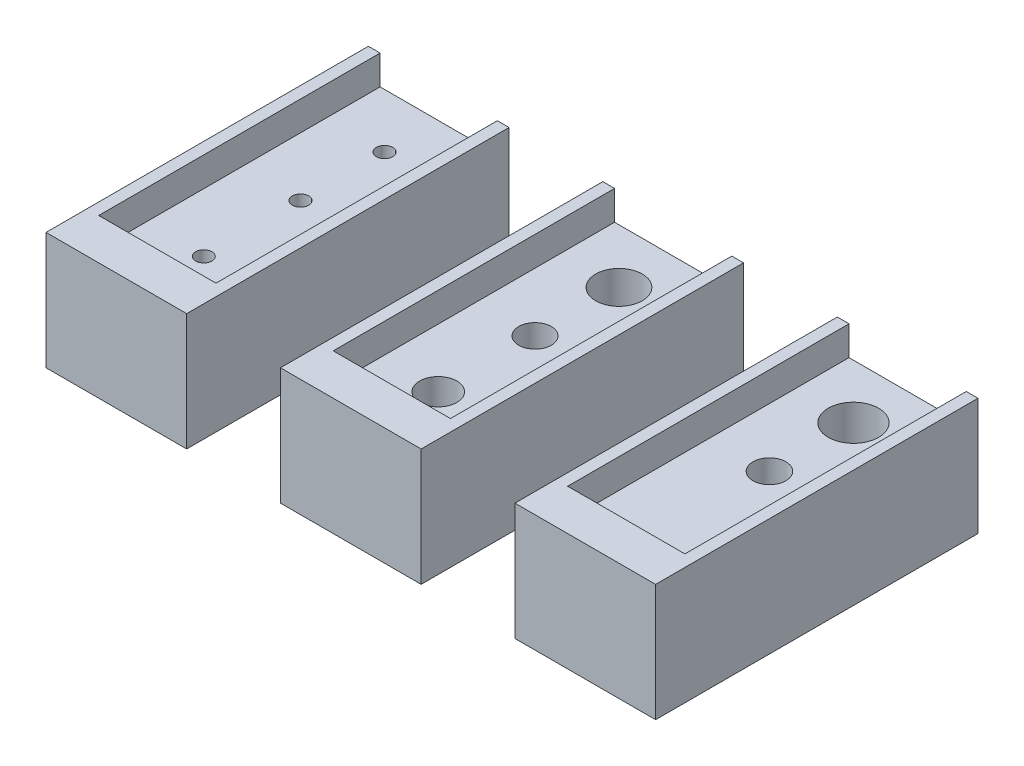
SolidWorks part; units mm, degrees
ref_plane "Front Plane" through (0, 0, 0) normal (0, 0, 1) x (1, 0, 0)
ref_plane "Top Plane" through (0, 0, 0) normal (0, 1, 0) x (1, 0, 0)
ref_plane "Right Plane" through (0, 0, 0) normal (1, 0, 0) x (0, 0, -1)
sketch "Sketch1" plane through (0, 0, 0) normal (0, 1, 0) x (1, 0, 0)
  line L0 (-20, 55) -> (0, 55) construction
  line L1 (0, 0) -> (20, 0)
  line L2 (0, 0) -> (0, 55)
  line L3 (0, 55) -> (20, 55)
  line L4 (20, 0) -> (20, 55)
  line L5 (10, 55) -> (10, 0) construction
  line L6 (0, 27.5) -> (20, 27.5) construction
  line L7 (40, 0) -> (60, 0)
  line L8 (40, 0) -> (40, 55)
  line L9 (40, 55) -> (60, 55)
  line L10 (60, 0) -> (60, 55)
  line L11 (50, 55) -> (50, 0) construction
  line L12 (40, 27.5) -> (60, 27.5) construction
  line L13 (-40, 0) -> (-20, 0)
  line L14 (-40, 0) -> (-40, 55)
  line L15 (-40, 55) -> (-20, 55)
  line L16 (-20, 0) -> (-20, 55)
  line L17 (-30, 55) -> (-30, 0) construction
  line L18 (-40, 27.5) -> (-20, 27.5) construction
  line L19 (20, 55) -> (40, 55) construction
  point P12 (-20, 37.5168)
  point P256 (-30, 27.5)
  point P304 (10, 27.5)
  point P350 (50, 27.5)
  dimension "D1" = 20
  dimension "D2" = 55
extrude "Boss-Extrude1" add sketch "Sketch1" along normal blind 15
sketch "Sketch2" plane through (0, 15, 0) normal (0, 1, 0) x (1, 0, 0)
  line L0 (-30, 55) -> (-30, 45.75) construction
  line L1 (-20, 55) -> (-40, 55) construction
  line L2 (-30, 45.75) -> (-30, 31.42) construction
  line L3 (-30, 31.42) -> (-30, 14.92) construction
  line L4 (10, 55) -> (10, 45.75) construction
  line L5 (20, 55) -> (0, 55) construction
  line L6 (10, 45.75) -> (10, 31.42) construction
  line L7 (10, 31.42) -> (10, 14.92) construction
  line L8 (10, 14.92) -> (50, 14.92) construction
  line L9 (50, 14.92) -> (50, 31.42) construction
  line L10 (50, 31.42) -> (50, 45.75) construction
  line L11 (50, 45.75) -> (50, 55) construction
  line L12 (60, 55) -> (40, 55) construction
  line L13 (50, 45.75) -> (10, 45.75) construction
  line L14 (10, 45.75) -> (-30, 45.75) construction
  line L15 (-30, 31.42) -> (10, 31.42) construction
  line L16 (10, 31.42) -> (50, 31.42) construction
  line L17 (-30, 14.92) -> (10, 14.92) construction
  circle A0 centre (-30, 45.75) radius 1.385
  circle A1 centre (-30, 31.42) radius 1.385
  circle A2 centre (-30, 14.92) radius 1.385
  circle A3 centre (50, 45.75) radius 4.3053
  circle A4 centre (50, 31.42) radius 2.8067
  circle A6 centre (10, 14.92) radius 3.175
  circle A7 centre (10, 31.42) radius 2.7781
  circle A8 centre (10, 45.75) radius 3.9688
  dimension "D4" = 2.77
  dimension "D5" = 5.6134
  dimension "D6" = 6.35
  dimension "D7" = 8.6106
  dimension "D8" = 5.5562
  dimension "D9" = 7.9375
  dimension "D1" = 16.5
  dimension "D2" = 14.33
  dimension "D3" = 9.25
extrude "Cut-Extrude1" cut sketch "Sketch2" against normal through all
sketch "Sketch3" plane through (0, 15, 0) normal (0, 1, 0) x (1, 0, 0)
  line L0 (-40, 55) -> (-40, 0) construction
  line L1 (-40, 7) -> (-20, 7)
  line L2 (-40, 7) -> (-40, 0)
  line L3 (-40, 0) -> (-20, 0)
  line L4 (-20, 7) -> (-20, 0)
  line L5 (-30, 0) -> (-30, 7) construction
  line L6 (-40, 3.5) -> (-20, 3.5) construction
  line L7 (0, 55) -> (0, 0) construction
  line L8 (0, 7) -> (20, 7)
  line L9 (0, 7) -> (0, 0)
  line L10 (0, 0) -> (20, 0)
  line L11 (20, 7) -> (20, 0)
  line L12 (10, 0) -> (10, 7) construction
  line L13 (0, 3.5) -> (20, 3.5) construction
  line L14 (40, 55) -> (40, 0) construction
  line L15 (40, 7) -> (60, 7)
  line L16 (40, 7) -> (40, 0)
  line L17 (40, 0) -> (60, 0)
  line L18 (60, 7) -> (60, 0)
  line L19 (50, 0) -> (50, 7) construction
  line L20 (40, 3.5) -> (60, 3.5) construction
  line L21 (-20, 55) -> (-40, 55) construction
  point P106 (10, 3.5)
  point P173 (50, 3.5)
  point P240 (-30, 3.5)
  dimension "D1" = 48
extrude "Boss-Extrude2" add sketch "Sketch3" along normal blind 5
sketch "Sketch4" plane through (0, 0, 0) normal (0, -1, 0) x (1, 0, 0)
  line L0 (-20, -55) -> (-40, -55) construction
  line L1 (-40, 0) -> (-42, 0)
  line L2 (-40, 0) -> (-40, -55)
  line L3 (-40, -55) -> (-42, -55)
  line L4 (-42, 0) -> (-42, -55)
  line L5 (-41, -55) -> (-41, 0) construction
  line L6 (-40, -27.5) -> (-42, -27.5) construction
  line L7 (-20, 0) -> (-18, 0)
  line L8 (-20, 0) -> (-20, -55)
  line L9 (-20, -55) -> (-18, -55)
  line L10 (-18, 0) -> (-18, -55)
  line L11 (-19, -55) -> (-19, 0) construction
  line L12 (-20, -27.5) -> (-18, -27.5) construction
  line L13 (0, 0) -> (-2, 0)
  line L14 (0, 0) -> (0, -55)
  line L15 (0, -55) -> (-2, -55)
  line L16 (-2, 0) -> (-2, -55)
  line L17 (-1, -55) -> (-1, 0) construction
  line L18 (0, -27.5) -> (-2, -27.5) construction
  line L19 (20, 0) -> (22, 0)
  line L20 (20, 0) -> (20, -55)
  line L21 (20, -55) -> (22, -55)
  line L22 (22, 0) -> (22, -55)
  line L23 (21, -55) -> (21, 0) construction
  line L24 (20, -27.5) -> (22, -27.5) construction
  line L25 (40, 0) -> (38, 0)
  line L26 (40, 0) -> (40, -55)
  line L27 (40, -55) -> (38, -55)
  line L28 (38, 0) -> (38, -55)
  line L29 (39, -55) -> (39, 0) construction
  line L30 (40, -27.5) -> (38, -27.5) construction
  line L31 (60, 0) -> (62, 0)
  line L32 (60, 0) -> (60, -55)
  line L33 (60, -55) -> (62, -55)
  line L34 (62, 0) -> (62, -55)
  line L35 (61, -55) -> (61, 0) construction
  line L36 (60, -27.5) -> (62, -27.5) construction
  point P24 (-40, -55)
  point P88 (61, -27.5)
  point P124 (-19, -27.5)
  point P149 (-1, -27.5)
  point P158 (39, -27.5)
  point P174 (21, -27.5)
  point P300 (-41, -27.5)
  dimension "D1" = 2
extrude "Boss-Extrude3" add sketch "Sketch4" against normal up to surface (20 mm away) up to face at (10, 20, -3.5)
